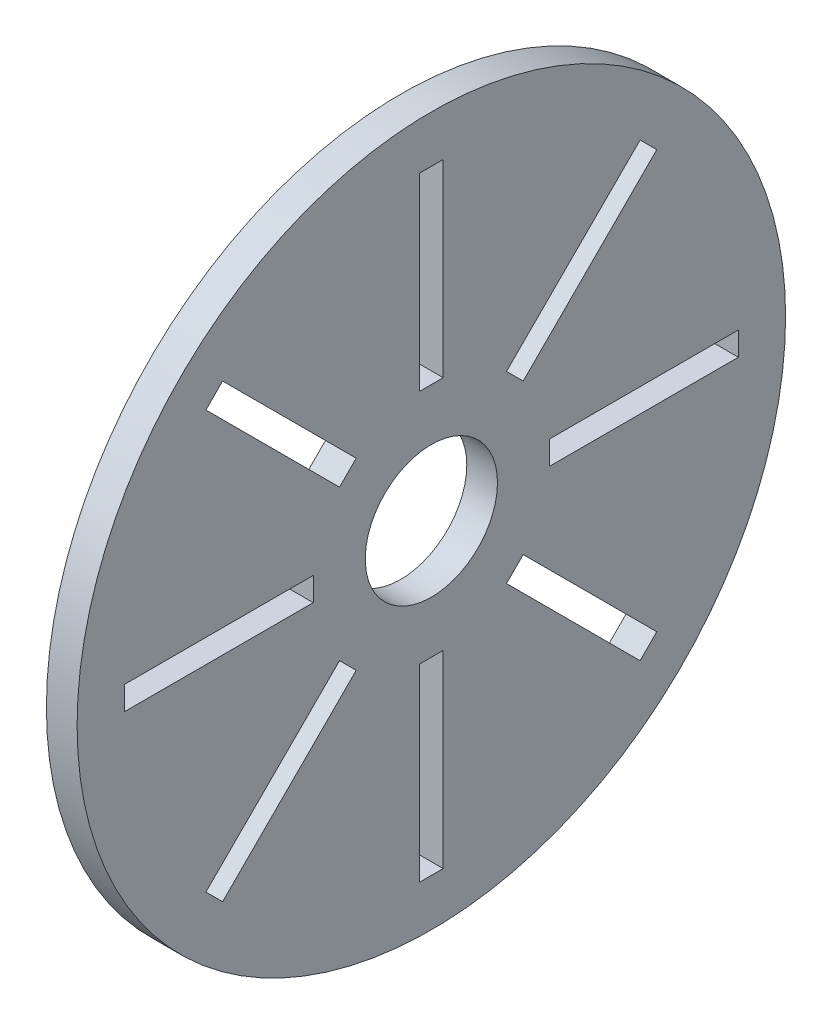
SolidWorks part; units mm, degrees
ref_plane "Front Plane" through (0, 0, 0) normal (0, 0, 1) x (1, 0, 0)
ref_plane "Top Plane" through (0, 0, 0) normal (0, 1, 0) x (1, 0, 0)
ref_plane "Right Plane" through (0, 0, 0) normal (1, 0, 0) x (0, 0, -1)
sketch "Sketch1" plane through (0, 0, 0) normal (1, 0, 0) x (0, 0, -1)
  circle A0 centre (0, 0) radius 15
  dimension "D1" = 30
extrude "Boss-Extrude1" add sketch "Sketch1" along normal blind 1.3
sketch "Sketch2" plane through (1.3, 0, 0) normal (1, 0, 0) x (0, 0, -1)
  circle A0 centre (0, 0) radius 2.8
  dimension "D1" = 5.6
extrude "Cut-Extrude1" cut sketch "Sketch2" against normal through all
sketch "Sketch3" plane through (1.3, 0, 0) normal (1, 0, 0) x (0, 0, -1)
  line L0 (0, 0.715) -> (0, -0.715) construction
  line L1 (-0.5, 13) -> (0.5, 13)
  line L2 (-0.5, 13) -> (-0.5, 5)
  line L3 (-0.5, 5) -> (0.5, 5)
  line L4 (0.5, 13) -> (0.5, 5)
  line L5 (-0.5, 13) -> (0.5, 5) construction
  line L6 (-0.5, 5) -> (0.5, 13) construction
  line L7 (0.715, 0) -> (-0.715, 0) construction
  line L8 (5, 0.5) -> (13, 0.5)
  line L9 (5, 0.5) -> (5, -0.5)
  line L10 (5, -0.5) -> (13, -0.5)
  line L11 (13, 0.5) -> (13, -0.5)
  line L12 (5, 0.5) -> (13, -0.5) construction
  line L13 (5, -0.5) -> (13, 0.5) construction
  line L14 (9.5459, 8.8388) -> (3.8891, 3.182)
  line L15 (-0.5, -5) -> (0.5, -5)
  line L16 (-0.5, -5) -> (-0.5, -13)
  line L17 (-0.5, -13) -> (0.5, -13)
  line L18 (0.5, -5) -> (0.5, -13)
  line L19 (-0.5, -5) -> (0.5, -13) construction
  line L20 (-0.5, -13) -> (0.5, -5) construction
  line L21 (-13, 0.5) -> (-5, 0.5)
  line L22 (-13, 0.5) -> (-13, -0.5)
  line L23 (-13, -0.5) -> (-5, -0.5)
  line L24 (-5, 0.5) -> (-5, -0.5)
  line L25 (-13, 0.5) -> (-5, -0.5) construction
  line L26 (-13, -0.5) -> (-5, 0.5) construction
  line L27 (8.8388, 9.5459) -> (3.182, 3.8891)
  line L28 (8.8388, 9.5459) -> (9.5459, 8.8388)
  line L29 (3.182, 3.8891) -> (3.8891, 3.182)
  line L30 (13, -0.5) -> (5, -0.5)
  line L31 (13, 0.5) -> (5, 0.5)
  line L32 (13, 0.5) -> (13, -0.5)
  line L33 (5, 0.5) -> (5, -0.5)
  line L34 (8.8388, -9.5459) -> (3.182, -3.8891)
  line L35 (9.5459, -8.8388) -> (3.8891, -3.182)
  line L36 (9.5459, -8.8388) -> (8.8388, -9.5459)
  line L37 (3.8891, -3.182) -> (3.182, -3.8891)
  line L38 (-0.5, -13) -> (-0.5, -5)
  line L39 (0.5, -13) -> (0.5, -5)
  line L40 (0.5, -13) -> (-0.5, -13)
  line L41 (0.5, -5) -> (-0.5, -5)
  line L42 (-9.5459, -8.8388) -> (-3.8891, -3.182)
  line L43 (-8.8388, -9.5459) -> (-3.182, -3.8891)
  line L44 (-8.8388, -9.5459) -> (-9.5459, -8.8388)
  line L45 (-3.182, -3.8891) -> (-3.8891, -3.182)
  line L46 (-13, 0.5) -> (-5, 0.5)
  line L47 (-13, -0.5) -> (-5, -0.5)
  line L48 (-13, -0.5) -> (-13, 0.5)
  line L49 (-5, -0.5) -> (-5, 0.5)
  line L50 (-8.8388, 9.5459) -> (-3.182, 3.8891)
  line L51 (-9.5459, 8.8388) -> (-3.8891, 3.182)
  line L52 (-9.5459, 8.8388) -> (-8.8388, 9.5459)
  line L53 (-3.8891, 3.182) -> (-3.182, 3.8891)
  point P0 (0, 9)
  point P7 (9, 0)
  point P14 (0, -9)
  point P19 (-9, 0)
  point P56 (0, 0)
  dimension "D1" = 1
  dimension "D2" = 1
  dimension "D3" = 1
  dimension "D4" = 1
  dimension "D5" = 8
  dimension "D6" = 8
  dimension "D7" = 8
  dimension "D8" = 8
  dimension "D9" = 5
  dimension "D10" = 5
  dimension "D11" = 5
  dimension "D12" = 5
  dimension "D13" = 8
extrude "Cut-Extrude2" cut sketch "Sketch3" against normal through all contours L43 L45 L42 L44 | L35 L37 L34 L36 | L51 L53 L50 L52 | L14 L29 L27 L28 | L4 L3 L2 L1 | L10 L11 L8 L9 | L16 L17 L18 L15 | L23 L24 L21 L22
